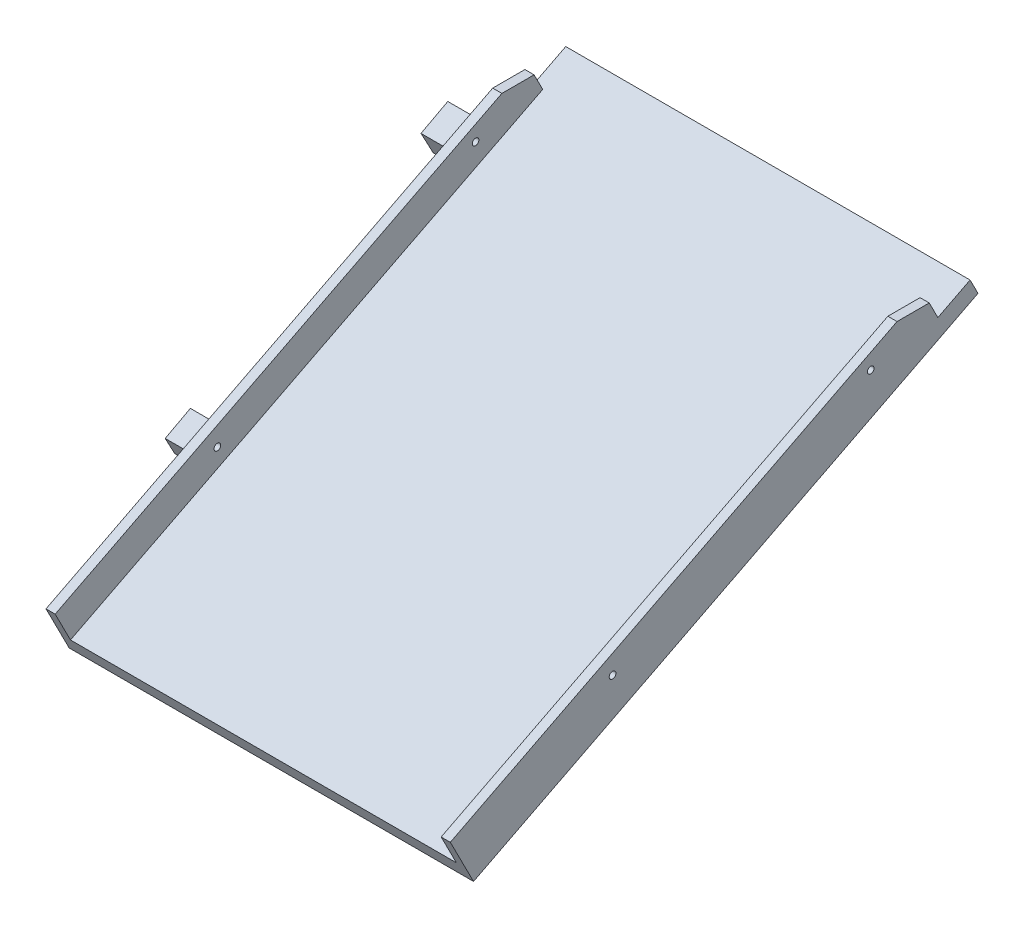
SolidWorks part; units mm, degrees
ref_plane "Front Plane" through (0, 0, 0) normal (0, 0, 1) x (1, 0, 0)
ref_plane "Top Plane" through (0, 0, 0) normal (0, 1, 0) x (1, 0, 0)
ref_plane "Right Plane" through (0, 0, 0) normal (1, 0, 0) x (0, 0, -1)
sketch "Sketch1" plane through (0, 0, 0) normal (1, 0, 0) x (0, 0, -1)
  line L0 (0, 0) -> (1214.1746, 618.6529)
  line L2 (-25.8775, 50.7874) -> (1188.2971, 669.4402)
  line L3 (1188.2971, 669.4402) -> (1214.1746, 618.6529)
  line L4 (0, 0) -> (-435.0785, -221.6836)
  line L5 (-435.0785, -221.6836) -> (-460.9559, -170.8962)
  line L6 (-25.8775, 50.7874) -> (-460.9559, -170.8962)
  dimension "D1" = 57
  dimension "D2" = 1362.7
  dimension "D3" = 488.3
extrude "Boss-Extrude1" add sketch "Sketch1" against normal blind 1321.8093
sketch "Sketch2" plane through (0, 50.7874, 25.8775) normal (0, 0.891, 0.454) x (1, 0, 0)
  line L0 (0, 0) -> (0, -488.3)
  line L2 (0, 0) -> (0, 1244.513)
  line L3 (0, 1244.513) -> (-67.8426, 1244.513)
  line L4 (-67.8426, 0) -> (-67.8426, 1244.513)
  line L9 (-67.8426, 0) -> (-67.8426, -488.3)
  line L10 (-1321.8093, -488.3) -> (0, -488.3) construction
  line L11 (-67.8426, -488.3) -> (0, -488.3)
  line L12 (-660.9047, -488.3) -> (-660.9047, 69.2596) construction
  line L13 (-1321.8093, 0) -> (-1321.8093, 1244.513)
  line L14 (-1321.8093, 1244.513) -> (-1253.9667, 1244.513)
  line L15 (-1253.9667, 0) -> (-1253.9667, 1244.513)
  line L16 (-1253.9667, 0) -> (-1253.9667, -488.3)
  line L17 (-1253.9667, -488.3) -> (-1321.8093, -488.3)
  line L18 (-1321.8093, 0) -> (-1321.8093, -488.3)
extrude "Boss-Extrude2" add sketch "Sketch2" along normal blind 110
sketch "Sketch3" plane through (-1321.8093, 0, 0) normal (-1, 0, 0) x (0, 0, 1)
  line L0 (-882.5636, 626.8588) -> (-795.043, 580.2368)
  line L1 (-795.043, 580.2368) -> (-834.9615, 505.3002)
  line L2 (-834.9615, 505.3002) -> (-922.4822, 551.9222)
  line L3 (-922.4822, 551.9222) -> (-882.5636, 626.8588)
  line L4 (-41.1338, 178.6317) -> (41.2274, 134.7581)
  line L5 (41.2274, 134.7581) -> (9.9828, 76.1046)
  line L6 (9.9828, 76.1046) -> (-72.3784, 119.9781)
  line L7 (-72.3784, 119.9781) -> (-51.6201, 114.116)
  line L8 (-51.6201, 114.116) -> (-72.3784, 119.9781)
  line L9 (-41.1338, 178.6317) -> (-72.3784, 119.9781)
extrude "Boss-Extrude4" add sketch "Sketch3" along normal blind 80
sketch "Sketch4" plane through (0, 0, 0) normal (1, 0, 0) x (0, 0, -1)
  circle A0 centre (19.453, 135.0172) radius 10.9358
  circle A1 centre (863.4628, 576.9362) radius 10.8051
extrude "Cut-Extrude1" cut sketch "Sketch4" against normal blind 1710 and the other way blind 390
sketch "Sketch5" plane through (0, 0, 0) normal (1, 0, 0) x (0, 0, -1)
  line L0 (1033.0528, 713.7952) -> (1054.7366, 671.2383)
  line L1 (1033.0528, 713.7952) -> (1082.9918, 615.7845) construction
  line L2 (1054.7366, 671.2383) -> (949.5303, 671.2383)
  line L3 (-510.8949, -72.8855) -> (1033.0528, 713.7952) construction
  line L4 (949.5303, 671.2383) -> (1033.0528, 713.7952)
extrude "Cut-Extrude2" cut sketch "Sketch5" against normal blind 1600 and the other way blind 10
sketch "Sketch7" plane through (0, -221.6836, 435.0785) normal (0, -0.454, 0.891) x (1, 0, 0)
  line L0 (-1321.8093, 167) -> (-1321.8093, 0) construction
  line L1 (-30, 57) -> (-1291.8093, 57)
  line L2 (-30, 57) -> (-30, 205.8266)
  line L3 (-30, 205.8266) -> (-1291.8093, 205.8266)
  line L4 (-1291.8093, 57) -> (-1291.8093, 205.8266)
  line L5 (0, 167) -> (0, 0) construction
  dimension "D1" = 30
  dimension "D2" = 30
extrude "Cut-Extrude3" cut sketch "Sketch7" against normal blind 1800 and the other way blind 1600
